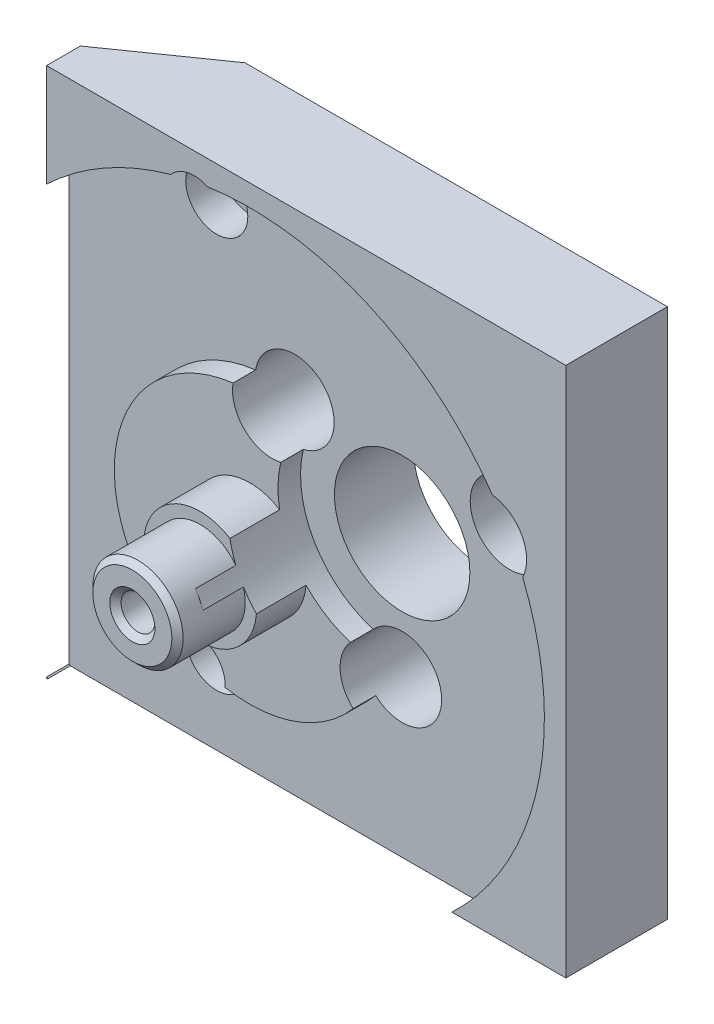
SolidWorks part; units mm, degrees
material "6061-T6 (SS)"
ref_plane "前视基准面" through (0, 0, 0) normal (0, 0, 1) x (1, 0, 0)
ref_plane "上视基准面" through (0, 0, 0) normal (0, 1, 0) x (1, 0, 0)
ref_plane "右视基准面" through (0, 0, 0) normal (1, 0, 0) x (0, 0, -1)
sketch "草图1" plane through (0, 0, 0) normal (0, 0, 1) x (1, 0, 0)
  line L1 (0, 0) -> (52, 0)
  line L2 (0, 0) -> (0, 47)
  line L3 (0, 47) -> (52, 47)
  line L4 (52, 0) -> (52, 47)
  dimension "D1" = 52
  dimension "D2" = 47
extrude "整体外形" add sketch "草图1" along normal blind 9
sketch "草图2" plane through (0, 0, 9) normal (0, 0, 1) x (1, 0, 0)
  line L0 (52, 0) -> (52, 47) construction
  line L1 (0, 0) -> (52, 0) construction
  circle A0 centre (24, 19) radius 26.1
  circle A1 centre (24, 19) radius 12
  dimension "D3" = 52.2
  dimension "D4" = 24
  dimension "D1" = 28
  dimension "D2" = 19
extrude "轮子连接凹槽" cut sketch "草图2" against normal blind 2
sketch "草图3" plane through (0, 0, 9) normal (0, 0, 1) x (1, 0, 0)
  circle A0 centre (24, 19) radius 5
  dimension "D1" = 10
extrude "轮子连接1" add sketch "草图3" along normal blind 4.4
sketch "草图4" plane through (0, 0, 13.4) normal (0, 0, 1) x (1, 0, 0)
  circle A0 centre (24, 19) radius 4
  dimension "D1" = 8
extrude "轮子连接2" add sketch "草图4" along normal blind 6
sketch "草图5" plane through (0, 0, 19.4) normal (0, 0, 1) x (1, 0, 0)
  circle A0 centre (24, 19) radius 1.5
  dimension "D1" = 3
extrude "轮子连接螺纹" cut sketch "草图5" against normal blind 10.1
cosmetic thread "装饰螺纹线2" parameters "D2"=4
chamfer "倒角1" distance 0.5 angle 45 2 edges at (28, 19, 19.4) (25.5, 19, 19.4)
sketch "草图6" plane through (0, 0, 7) normal (0, 0, 1) x (1, 0, 0)
  line L1 (52, 0) -> (52, 47) construction
  circle A0 centre (35.5, 24.8447) radius 6
  point P2 (24, 19)
  dimension "D2" = 12
  dimension "D1" = 12.9
  dimension "D3" = 16.5
extrude "电机轴孔位" cut sketch "草图6" against normal through all and the other way through all
sketch "草图7" plane through (0, 0, 7) normal (0, 0, 1) x (1, 0, 0)
  line L0 (35.5, 24.8447) -> (25.9737, 30.3447) construction
  line L1 (35.5, 24.8447) -> (45.0263, 30.3447) construction
  line L2 (35.5, 24.8447) -> (35.5, 13.8447) construction
  circle A0 centre (35.5, 24.8447) radius 11 construction
  circle A2 centre (25.9737, 30.3447) radius 1.6
  circle A3 centre (45.0263, 30.3447) radius 1.6
  circle A4 centre (35.5, 13.8447) radius 1.6
  dimension "D1" = 22
  dimension "D3" = 120
  dimension "D4" = 3.2
  dimension "D2" = 120
extrude "电机孔位" cut sketch "草图7" against normal through all and the other way through all
sketch "草图8" plane through (0, 0, 7) normal (0, 0, 1) x (1, 0, 0)
  circle A0 centre (45.0263, 30.3447) radius 3.5
  dimension "D1" = 7
extrude "电机螺丝上安装孔位" cut sketch "草图8" against normal blind 5.5 and the other way through all
pattern_circular "阵列(圆周)1" count 3 every 120 about axis through (35.5, 24.8447, 0) along (0, 0, 1) of "电机螺丝上安装孔位"
sketch "草图9" plane through (0, 0, 7) normal (0, 0, 1) x (1, 0, 0)
  line L0 (19.0759, 42.3447) -> (19.0759, 7.3447) construction
  circle A0 centre (35.5, 24.8447) radius 24 construction
  circle A1 centre (19.0759, 42.3447) radius 1
  circle A2 centre (19.0759, 7.3447) radius 1
  dimension "D1" = 48
  dimension "D3" = 2
  dimension "D2" = 35
extrude "编码器孔位" cut sketch "草图9" against normal through all
sketch "草图10" plane through (0, 0, 7) normal (0, 0, 1) x (1, 0, 0)
  circle A0 centre (19.0759, 42.3447) radius 2.75
  circle A1 centre (19.0759, 7.3447) radius 2.75
  dimension "D1" = 5.5
  dimension "D2" = 5.5
extrude "编码器孔位上部分" cut sketch "草图10" against normal blind 3 and the other way through all
sketch "草图11" plane through (0, 0, 0) normal (0, -1, 0) x (1, 0, 0)
  line L0 (6.1056, 7) -> (41.8944, 7) construction
  line L1 (52, 9) -> (52, 0) construction
  circle A0 centre (15, 3.5) radius 1
  circle A1 centre (50, 3.5) radius 1
  circle A2 centre (32, 3.5) radius 1
  dimension "D2" = 2
  dimension "D5" = 2
  dimension "D7" = 2
  dimension "D1" = 3.5
  dimension "D3" = 37
  dimension "D4" = 35
  dimension "D6" = 17
extrude "切除-拉伸9" cut sketch "草图11" against normal blind 7.5
cosmetic thread "装饰螺纹线3" parameters "D2"=3
cosmetic thread "装饰螺纹线4" parameters "D2"=3
cosmetic thread "装饰螺纹线5" parameters "D2"=3
sketch "草图12" plane through (0, 0, 0) normal (0, -1, 0) x (1, 0, 0)
  line L0 (0, 8) -> (11.4252, 0)
  line L1 (0, 9) -> (0, 0) construction
  line L2 (0, 0) -> (52, 0) construction
  line L3 (0, 9) -> (6.1056, 9) construction
  line L4 (0, 8) -> (0, 0)
  line L5 (0, 0) -> (11.4252, 0)
  dimension "D1" = 1
  dimension "D2" = 35
extrude "修改外形1" cut sketch "草图12" against normal through all
sketch "草图13" plane through (0, 47, 0) normal (0, 1, 0) x (1, 0, 0)
  line L0 (0, -9) -> (6, -9)
  line L1 (52, -9) -> (0, -9) construction
  line L2 (6, -9) -> (6, -6)
  line L3 (6, -6) -> (14.5689, 0)
  line L4 (52, 0) -> (11.4252, 0) construction
  line L5 (14.5689, 0) -> (11.4252, 0)
  line L7 (0, -8) -> (0, -9)
  line L8 (0, -8) -> (11.4252, 0)
  line L9 (11.4252, 0) -> (0, -8) construction
  dimension "D1" = 6
  dimension "D2" = 3
extrude "修改外形2" cut sketch "草图13" against normal through all
sketch "草图14" plane through (0, 0, 7) normal (0, 0, 1) x (1, 0, 0)
  circle A0 centre (35.5, 24.8447) radius 9
  dimension "D1" = 18
extrude "切除-拉伸10" cut sketch "草图14" along normal blind 10
